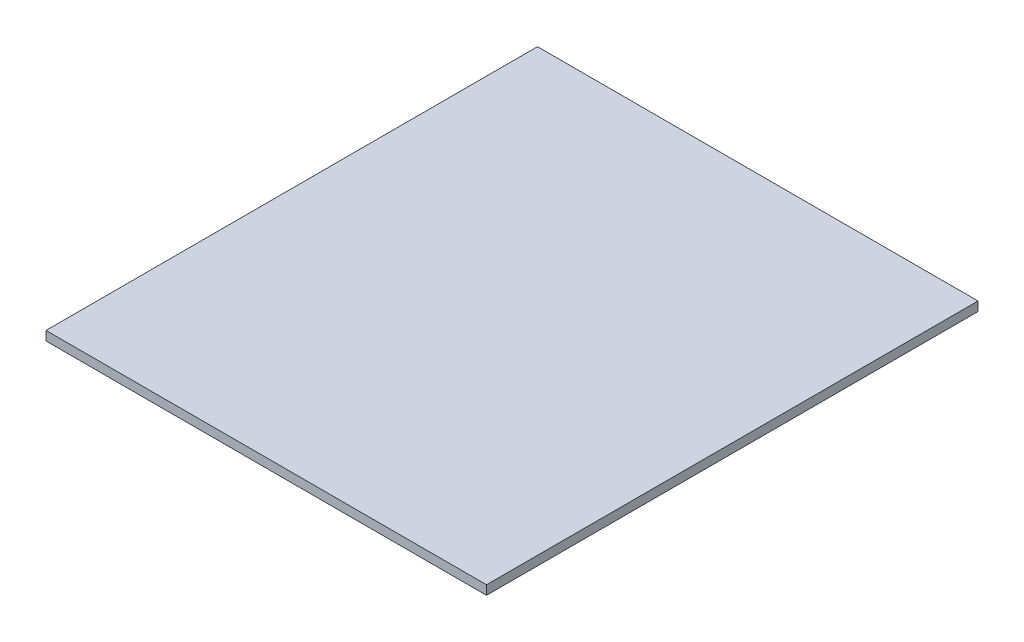
SolidWorks part; units mm, degrees
material "Plywood"
ref_plane "Front Plane" through (0, 0, 0) normal (0, 0, 1) x (1, 0, 0)
ref_plane "Top Plane" through (0, 0, 0) normal (0, 1, 0) x (1, 0, 0)
ref_plane "Right Plane" through (0, 0, 0) normal (1, 0, 0) x (0, 0, -1)
sketch "Sketch1" plane through (0, 0, 0) normal (0, 1, 0) x (1, 0, 0)
  line L1 (-438.9437, -489.7437) -> (438.9438, -489.7437)
  line L2 (-438.9437, -489.7437) -> (-438.9437, 489.7437)
  line L3 (-438.9437, 489.7437) -> (438.9438, 489.7437)
  line L4 (438.9438, -489.7437) -> (438.9438, 489.7437)
  line L5 (-438.9437, -489.7437) -> (438.9438, 489.7437) construction
  line L6 (-438.9437, 489.7437) -> (438.9438, -489.7437) construction
  point P0 (0, 0)
  dimension "D1" = 877.8875
  dimension "D2" = 979.4875
extrude "Boss-Extrude1" add sketch "Sketch1" along normal blind 18.2562
